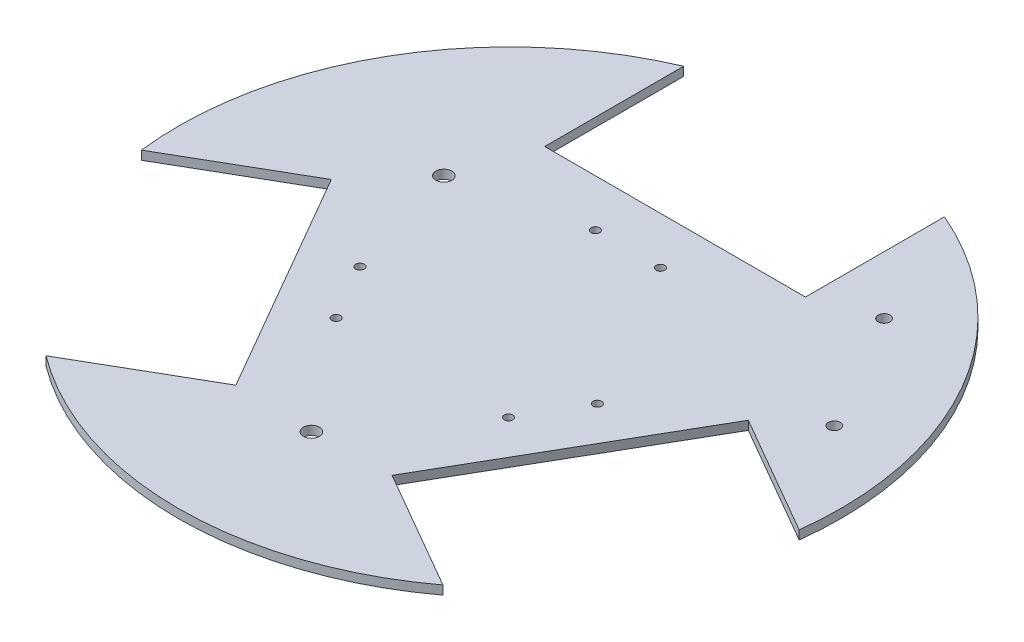
SolidWorks part; units mm, degrees
ref_plane "Front" through (0, 0, 0) normal (0, 0, 1) x (1, 0, 0)
ref_plane "Top" through (0, 0, 0) normal (0, 1, 0) x (1, 0, 0)
ref_plane "Right" through (0, 0, 0) normal (1, 0, 0) x (0, 0, -1)
sketch "Sketch1" plane through (0, 0, 0) normal (0, 1, 0) x (1, 0, 0)
  line L0 (-35, 44.4119) -> (-35, 81.7203)
  line L1 (-35, 44.4119) -> (35, 44.4119)
  line L2 (35, 44.4119) -> (35, 81.7203)
  line L3 (55.9618, 8.1049) -> (88.2719, -10.5493)
  line L4 (55.9618, 8.1049) -> (20.9618, -52.5168)
  line L5 (20.9618, -52.5168) -> (53.2719, -71.171)
  line L12 (-20.9618, -52.5168) -> (-53.2719, -71.171)
  line L15 (-20.9618, -52.5168) -> (-55.9618, 8.1049)
  line L16 (-55.9618, 8.1049) -> (-88.2719, -10.5493)
  arc A0 (88.2719, -10.5493) -> (35, 81.7203) centre (0, 0) ccw
  arc A1 (-35, 81.7203) -> (-88.2719, -10.5493) centre (0, 0) ccw
  arc A2 (-53.2719, -71.171) -> (53.2719, -71.171) centre (0, 0) ccw
  circle A3 centre (-41.7474, 24.1029) radius 2.1463
  circle A4 centre (-8.7312, 31.75) radius 1.1494
  circle A5 centre (50.5294, 49.9814) radius 1.5875
  circle A6 centre (0, -53.2058) radius 2.1463
  circle A7 centre (68.7857, 18.3606) radius 1.5875
  circle A8 centre (8.7312, 31.75) radius 1.1493
  circle A9 centre (31.8619, -8.3135) radius 1.1493
  circle A10 centre (23.1307, -23.4365) radius 1.1494
  circle A11 centre (-31.8619, -8.3135) radius 1.1494
  circle A12 centre (-23.1307, -23.4365) radius 1.1494
  point P15 (-8.1441, -4.702)
  point P16 (0, 0)
  point P25 (0, 0)
  dimension "D1" = 3
  dimension "D4" = 88.9
  dimension "D5" = 60
  dimension "D6" = 60
extrude "Boss-Extrude1" add sketch "Sketch1" along normal blind 2.3622
